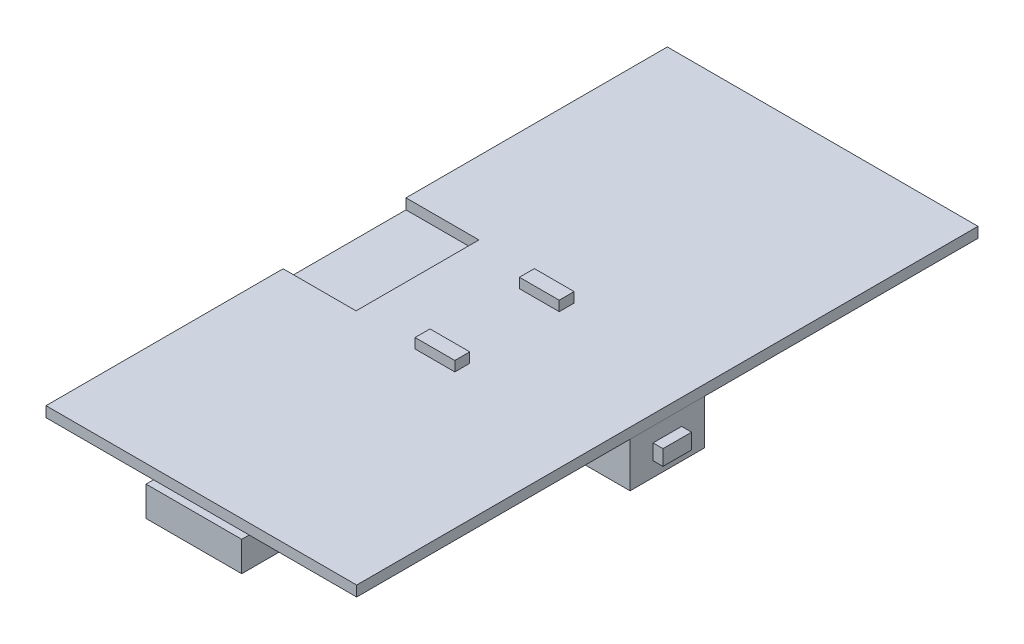
SolidWorks part; units mm, degrees
other "TactSwitch"
ref_plane "Front Plane" through (0, 0, 0) normal (0, 0, 1) x (1, 0, 0)
ref_plane "Top Plane" through (0, 0, 0) normal (0, 1, 0) x (1, 0, 0)
ref_plane "Right Plane" through (0, 0, 0) normal (1, 0, 0) x (0, 0, -1)
sketch "Sketch1" plane through (0, 0, 0) normal (0, 1, 0) x (1, 0, 0)
  line L1 (0, 0) -> (0, -66.7312) construction
  line L6 (-15.875, 31.75) -> (15.875, 31.75)
  line L8 (-15.875, 31.75) -> (-15.875, -31.75)
  line L9 (-15.875, -31.75) -> (15.875, -31.75)
  line L10 (15.875, 31.75) -> (15.875, -31.75)
  line L11 (-15.875, 31.75) -> (15.875, -31.75) construction
  line L12 (-15.875, -31.75) -> (15.875, 31.75) construction
  dimension "D10" = 31.75
  dimension "D11" = 63.5
extrude "BareBoard" add sketch "Sketch1" along normal blind 1.0668
sketch "Sketch2" plane through (0, 0, 0) normal (0, -1, 0) x (1, 0, 0)
  line L0 (-15.875, 31.75) -> (15.875, 31.75) construction
  line L1 (-4.8895, 32.512) -> (4.8895, 32.512)
  line L2 (-4.8895, 32.512) -> (-4.8895, 26.162)
  line L3 (-4.8895, 26.162) -> (4.8895, 26.162)
  line L4 (4.8895, 32.512) -> (4.8895, 26.162)
  line L5 (0, 0) -> (0, 28.5084) construction
  point P11 (-5.4115, 31.75)
  point P14 (-5.4115, 31.75)
  dimension "D1" = 9.779
  dimension "D2" = 6.35
  dimension "D3" = 0.762
extrude "USB" add sketch "Sketch2" along normal blind 3.048 separate body
sketch "Sketch3" plane through (0, 1.0668, 0) normal (0, 1, 0) x (1, 0, 0)
  line L0 (0, 0) -> (0, 26.2894) construction
  line L1 (-2.032, 4.318) -> (2.032, 4.318)
  line L2 (-2.032, 4.318) -> (-2.032, 2.794)
  line L3 (-2.032, 2.794) -> (2.032, 2.794)
  line L4 (2.032, 4.318) -> (2.032, 2.794)
  line L5 (-2.032, -6.35) -> (2.032, -6.35)
  line L6 (-2.032, -6.35) -> (-2.032, -7.874)
  line L7 (-2.032, -7.874) -> (2.032, -7.874)
  line L8 (2.032, -6.35) -> (2.032, -7.874)
  dimension "D1" = 4.064
  dimension "D2" = 1.524
  dimension "D3" = 2.794
  dimension "D4" = 6.35
extrude "SideFire LEDs" add sketch "Sketch3" along normal blind 1.016 separate body
sketch "Sketch4" plane through (0, 0, 0) normal (0, -1, 0) x (1, 0, 0)
  line L0 (-15.875, -31.75) -> (-15.875, 31.75) construction
  line L1 (-15.875, 7.5169) -> (4.445, 7.5169)
  line L2 (-15.875, 7.5169) -> (-15.875, -5.1831)
  line L3 (-15.875, -5.1831) -> (4.445, -5.1831)
  line L4 (4.445, 7.5169) -> (4.445, -5.1831)
  dimension "D1" = 12.7
  dimension "D3" = 20.32
extrude "BLE Radio" add sketch "Sketch4" along normal blind 2.794 separate body
sketch "Sketch5" plane through (0, -2.794, 0) normal (0, -1, 0) x (1, 0, 0)
  line L0 (-15.875, -5.1831) -> (4.445, -5.1831) construction
  line L1 (-15.875, 7.5169) -> (-9.525, 7.5169)
  line L2 (-15.875, 7.5169) -> (-15.875, -5.1831)
  line L3 (-15.875, -5.1831) -> (-9.525, -5.1831)
  line L4 (-9.525, 7.5169) -> (-9.525, -5.1831)
  dimension "D1" = 6.35
extrude "Cut-BLE1" cut sketch "Sketch5" against normal blind 2.032
sketch "Sketch6" plane through (0, 1.0668, 0) normal (0, 1, 0) x (1, 0, 0)
  line L0 (4.445, -7.5169) -> (-15.875, -7.5169) construction
  line L1 (-21.121, 5.04) -> (-8.421, 5.04)
  line L2 (-21.121, 5.04) -> (-21.121, -7.5169)
  line L3 (-21.121, -7.5169) -> (-8.421, -7.5169)
  line L4 (-8.421, 5.04) -> (-8.421, -7.5169)
  dimension "D1" = 12.7
  dimension "D2" = 8.421
extrude "Cut-BLE2" cut sketch "Sketch6" against normal up to surface (1.0668 mm away) up to face at (0, 0, 0)
sketch "Sketch7" plane through (0, 0, 0) normal (0, -1, 0) x (1, 0, 0)
  line L0 (0, 0) -> (31.0719, 0) construction
  line L1 (9.525, 3.81) -> (15.875, 3.81)
  line L2 (9.525, 3.81) -> (9.525, -3.81)
  line L3 (9.525, -3.81) -> (15.875, -3.81)
  line L4 (15.875, 3.81) -> (15.875, -3.81)
  line L5 (9.525, 3.81) -> (15.875, -3.81) construction
  line L6 (9.525, -3.81) -> (15.875, 3.81) construction
  line L7 (15.875, 31.75) -> (15.875, -31.75) construction
  point P0 (12.7, 0)
  dimension "D1" = 7.62
  dimension "D2" = 6.35
extrude "SwitchBase" add sketch "Sketch7" along normal blind 4.572 separate body
sketch "Sketch8" plane through (15.875, 0, 0) normal (1, 0, 0) x (0, 0, -1)
  line L0 (3.81, -2.286) -> (-3.81, -2.286) construction
  line L1 (3.81, -4.572) -> (3.81, 0) construction
  line L2 (-3.81, -4.572) -> (-3.81, 0) construction
  line L3 (0, -4.572) -> (0, 0) construction
  line L4 (3.81, -4.572) -> (-3.81, -4.572) construction
  line L5 (3.81, 0) -> (-3.81, 0) construction
  line L7 (-1.4605, -1.4986) -> (1.4605, -1.4986)
  line L8 (-1.4605, -1.4986) -> (-1.4605, -3.0734)
  line L9 (-1.4605, -3.0734) -> (1.4605, -3.0734)
  line L10 (1.4605, -1.4986) -> (1.4605, -3.0734)
  line L11 (-1.4605, -1.4986) -> (1.4605, -3.0734) construction
  line L12 (-1.4605, -3.0734) -> (1.4605, -1.4986) construction
  point P12 (0, -2.286)
  dimension "D1" = 1.5748
  dimension "D2" = 2.921
extrude "ButtonSwitch" add sketch "Sketch8" along normal blind 1.016
